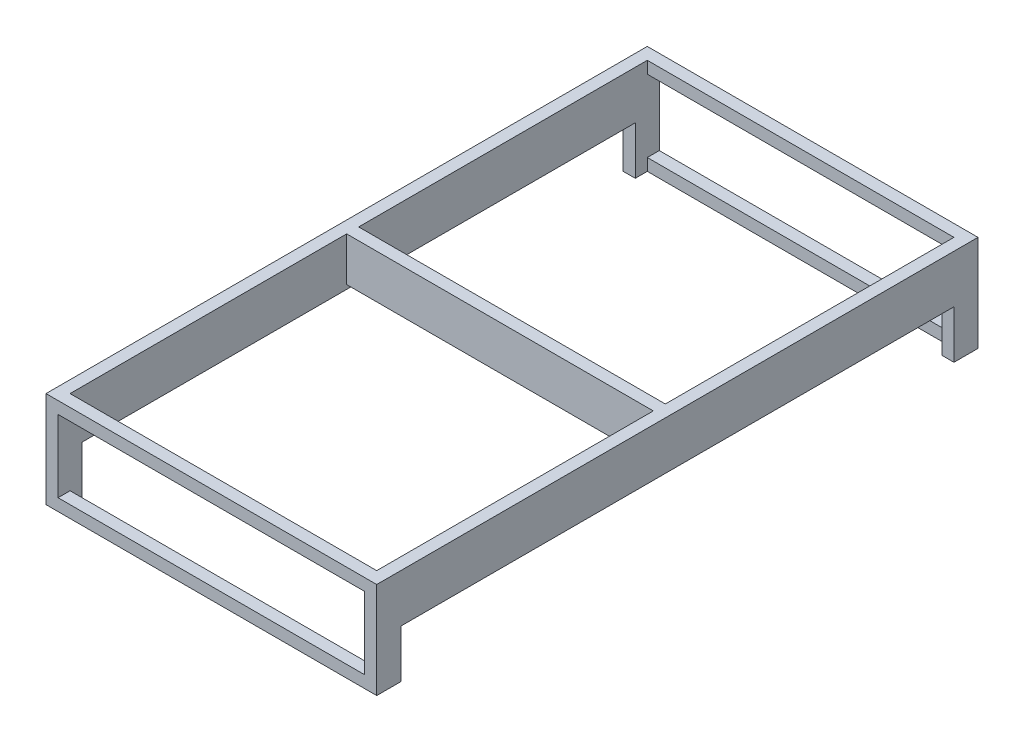
SolidWorks part; units mm, degrees
ref_plane "Front Plane" through (0, 0, 0) normal (0, 0, 1) x (1, 0, 0)
ref_plane "Top Plane" through (0, 0, 0) normal (0, 1, 0) x (1, 0, 0)
ref_plane "Right Plane" through (0, 0, 0) normal (1, 0, 0) x (0, 0, -1)
sketch "Sketch1" plane through (0, 0, 0) normal (0, 0, 1) x (1, 0, 0)
  line L0 (-20, -20) -> (-20, 140)
  line L1 (0, 0) -> (510, 0)
  line L2 (0, 0) -> (0, 120)
  line L3 (0, 120) -> (510, 120)
  line L4 (510, 0) -> (510, 120)
  line L5 (-20, 140) -> (530, 140)
  line L6 (530, -20) -> (530, 140)
  line L7 (-20, -20) -> (530, -20)
  dimension "D1" = 120
  dimension "D2" = 510
  dimension "D3" = 20
extrude "Boss-Extrude1" add sketch "Sketch1" along normal blind 1000
sketch "Sketch2" plane through (-20, 0, 0) normal (-1, 0, 0) x (0, 0, 1)
  line L0 (1000, -20) -> (0, -20) construction
  line L1 (40, 60) -> (960, 60)
  line L2 (40, 60) -> (40, -20)
  line L3 (40, -20) -> (960, -20)
  line L4 (960, 60) -> (960, -20)
  line L5 (0, 140) -> (0, -20) construction
  line L6 (1000, 140) -> (1000, -20) construction
  line L7 (1000, 140) -> (0, 140) construction
  dimension "D1" = 40
  dimension "D2" = 40
  dimension "D3" = 80
extrude "Cut-Extrude1" cut sketch "Sketch2" against normal blind 1000
sketch "Sketch3" plane through (0, 140, 0) normal (0, 1, 0) x (1, 0, 0)
  line L0 (510, -20) -> (0, -20)
  line L1 (0, -20) -> (0, -980)
  line L2 (0, -980) -> (510, -980)
  line L3 (510, -980) -> (510, -20)
  line L4 (530, 0) -> (-20, 0)
  line L5 (-20, 0) -> (-20, -1000)
  line L6 (-20, -1000) -> (530, -1000)
  line L7 (530, -1000) -> (530, 0)
  line L8 (530, 0) -> (-20, 0)
  line L9 (-20, 0) -> (-20, -1000)
  line L10 (-20, -1000) -> (530, -1000)
  line L11 (530, -1000) -> (530, 0)
  dimension "D1" = 0
  dimension "D2" = 20
extrude "Cut-Extrude3" cut sketch "Sketch3" against normal blind 1000 contours L2 L3 L0 L1
sketch "Sketch4" plane through (0, 140, 0) normal (0, 1, 0) x (1, 0, 0)
  line L0 (-20, -1000) -> (-20, 0) construction
  line L1 (-20, -520) -> (530, -520)
  line L2 (-20, -520) -> (-20, -500)
  line L3 (-20, -500) -> (530, -500)
  line L4 (530, -520) -> (530, -500)
  line L5 (530, -1000) -> (530, 0) construction
  line L6 (530, -1000) -> (-20, -1000) construction
  dimension "D1" = 500
  dimension "D2" = 20
extrude "Boss-Extrude2" add sketch "Sketch4" against normal blind 73
